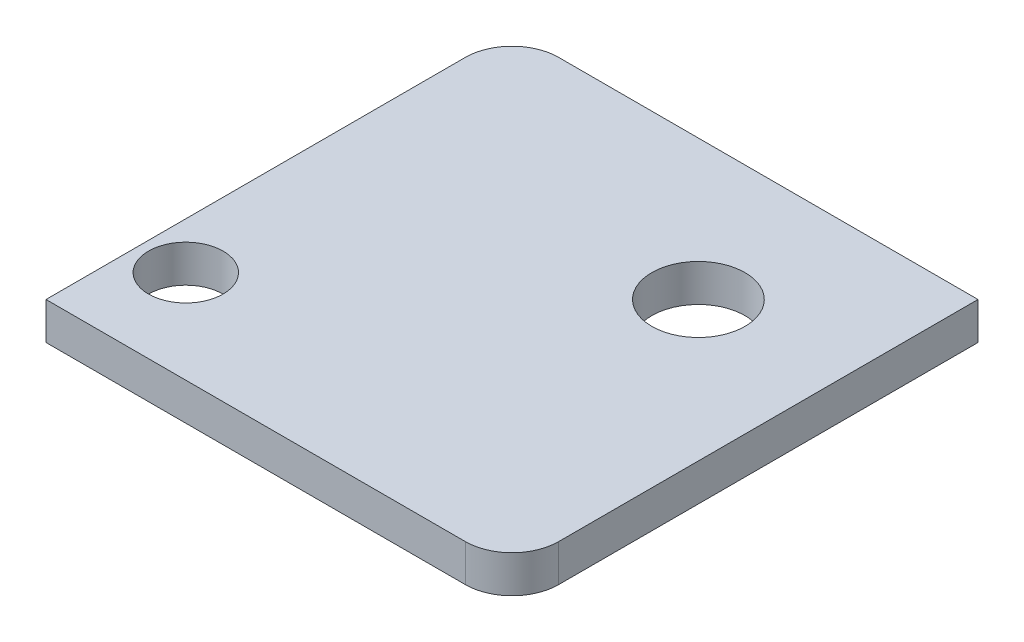
SolidWorks part; units mm, degrees
ref_plane "Front Plane" through (0, 0, 0) normal (0, 0, 1) x (1, 0, 0)
ref_plane "Top Plane" through (0, 0, 0) normal (0, 1, 0) x (1, 0, 0)
ref_plane "Right Plane" through (0, 0, 0) normal (1, 0, 0) x (0, 0, -1)
sketch "Sketch1" plane through (0, 0, 0) normal (0, 1, 0) x (1, 0, 0)
  line L0 (0, 0) -> (0, 45)
  line L3 (45, 0) -> (0, 0)
  line L4 (5, 50) -> (50, 50)
  line L5 (50, 50) -> (50, 5)
  circle A2 centre (5, 10) radius 4
  circle A4 centre (35, 35) radius 5
  arc A8 (45, 0) -> (50, 5) centre (45, 5) ccw
  arc A9 (0, 45) -> (5, 50) centre (5, 45) cw
  point P8 (0, 50)
  dimension "D1" = 50
  dimension "D2" = 8
  dimension "D5" = 10
  dimension "D7" = 15
  dimension "D9" = 5
  dimension "D3" = 5
  dimension "D4" = 10
  dimension "D6" = 15
  dimension "D8" = 50
extrude "Boss-Extrude1" add sketch "Sketch1" along normal blind 4
